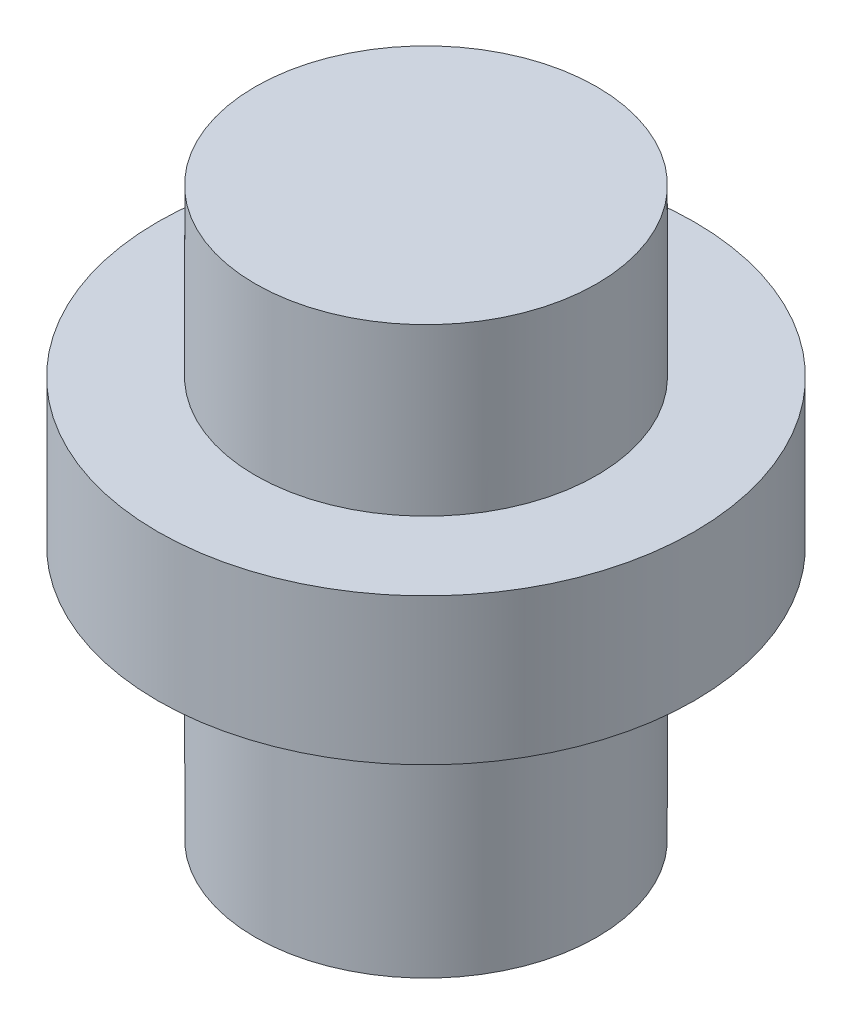
SolidWorks part; units mm, degrees
ref_plane "前视基准面" through (0, 0, 0) normal (0, 0, 1) x (1, 0, 0)
ref_plane "上视基准面" through (0, 0, 0) normal (0, 1, 0) x (1, 0, 0)
ref_plane "右视基准面" through (0, 0, 0) normal (1, 0, 0) x (0, 0, -1)
other "Configuration Table"
ref_plane "基准面1" through (0, -8.55, 0) normal (0, -1, 0) x (-1, 0, 0)
sketch "草图1" plane through (0, -8.55, 0) normal (0, -1, 0) x (-1, 0, 0)
  circle A0 centre (-13.6355, 19.6206) radius 1.75 construction
  circle A1 centre (-13.6355, 19.6206) radius 1.75
extrude "凸台-拉伸1" add sketch "草图1" along normal blind 5.8
sketch "草图2" plane through (0, -10.25, 0) normal (0, 1, 0) x (1, 0, 0)
  circle A0 centre (13.6355, 19.6206) radius 1.75 construction
  circle A3 centre (13.6355, 19.6206) radius 1.75
extrude "拉伸-薄壁1" add sketch "草图2" against normal blind 1.5 thin
